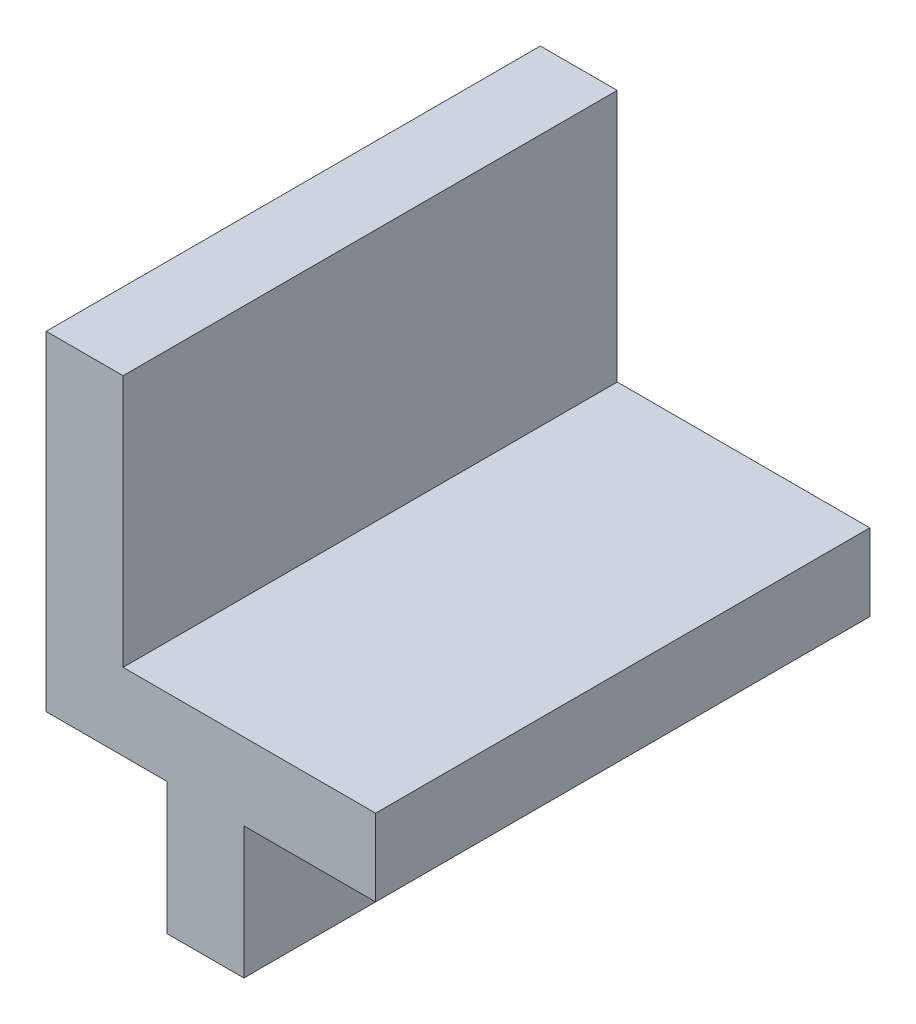
SolidWorks part; units mm, degrees
ref_plane "Спереди" through (0, 0, 0) normal (0, 0, 1) x (1, 0, 0)
ref_plane "Сверху" through (0, 0, 0) normal (0, 1, 0) x (1, 0, 0)
ref_plane "Справа" through (0, 0, 0) normal (1, 0, 0) x (0, 0, -1)
sketch "Эскиз1" plane through (0, 0, 0) normal (0, 0, 1) x (1, 0, 0)
  line L0 (0, 0) -> (-30, 0)
  line L1 (-30, 0) -> (-30, 30)
  line L2 (-30, 30) -> (-23, 30)
  line L3 (-23, 30) -> (-23, 7)
  line L4 (-23, 7) -> (0, 7)
  line L5 (0, 7) -> (0, 0)
  line L6 (0, 0) -> (0.0628, -0.2337)
  dimension "D1" = 30
  dimension "D8" = 7
extrude "Бобышка-Вытянуть1" add sketch "Эскиз1" along normal blind 45
sketch "Эскиз2" plane through (0, 0, 45) normal (0, 0, 1) x (1, 0, 0)
  line L0 (0, 0) -> (-30, 0) construction
  line L1 (-19, 0) -> (-12, 0)
  line L2 (-19, 0) -> (-19, -12)
  line L3 (-19, -12) -> (-12, -12)
  line L4 (-12, 0) -> (-12, -12)
  line L5 (0, 7) -> (0, 0) construction
  point P6 (0, 3.5)
  dimension "D1" = 12
  dimension "D2" = 7
  dimension "D3" = 12
extrude "Бобышка-Вытянуть2" add sketch "Эскиз2" against normal up to surface (45 mm away) up to face at (-17.6667, 12.3333, 0)
